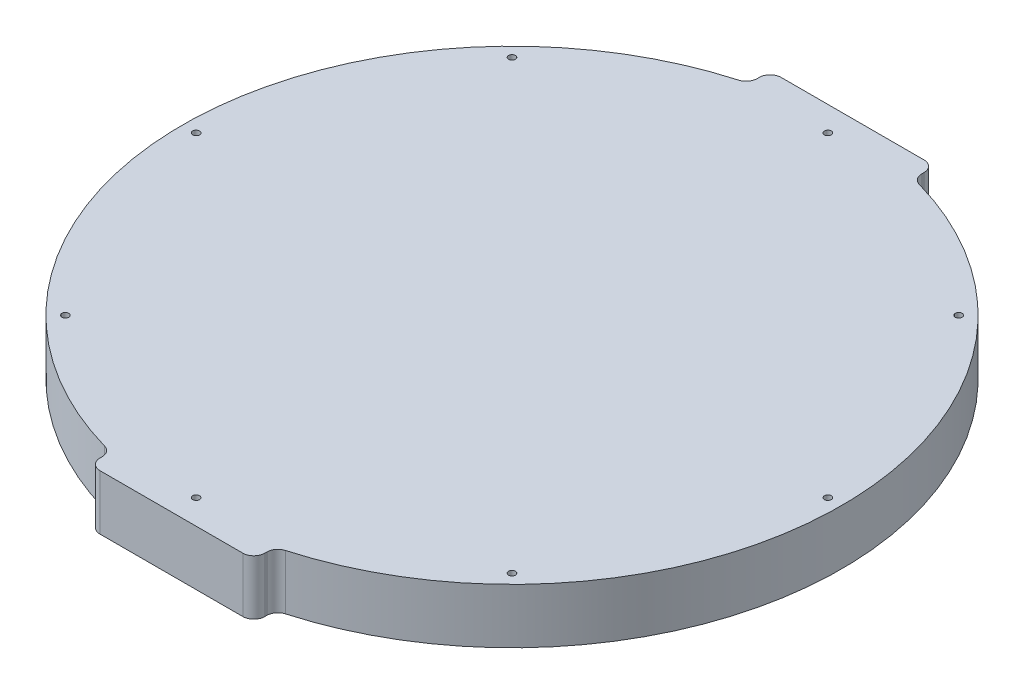
SolidWorks part; units mm, degrees
material "6061 Alloy"
ref_plane "Front Plane" through (0, 0, 0) normal (0, 0, 1) x (1, 0, 0)
ref_plane "Top Plane" through (0, 0, 0) normal (0, 1, 0) x (1, 0, 0)
ref_plane "Right Plane" through (0, 0, 0) normal (1, 0, 0) x (0, 0, -1)
sketch "Sketch2" plane through (0, 0, 0) normal (0, 1, 0) x (1, 0, 0)
  circle A0 centre (0, 0) radius 76.2
extrude "Boss-Extrude1" add sketch "Sketch2" along normal blind 12.7
sketch "Sketch3" plane through (0, 0, 0) normal (0, 0, 1) x (1, 0, 0)
  line L0 (0, 0) -> (-19.05, 0)
  line L1 (-19.05, 0) -> (-19.05, 12.7)
  line L2 (-19.05, 12.7) -> (19.05, 12.7)
  line L3 (19.05, 12.7) -> (19.05, 0)
  line L4 (0, 0) -> (19.05, 0)
extrude "Boss-Extrude2" add sketch "Sketch3" along normal blind 78.74 and the other way blind 78.74
fillet "Fillet1" radius 2.54 8 edges at (19.05, 6.35, 73.7803) (19.05, 6.35, -73.7803) (19.05, 6.35, 78.74) (-19.05, 6.35, -73.7803) (-19.05, 6.35, 73.7803) (-19.05, 6.35, 78.74) (-19.05, 6.35, -78.74) (19.05, 6.35, -78.74)
sketch "Sketch4" plane through (0, 12.7, 0) normal (0, 1, 0) x (1, 0, 0)
  circle A0 centre (73.025, 0) radius 0.7937
  circle A1 centre (51.6365, -51.6365) radius 0.7937
  circle A2 centre (0, -73.025) radius 0.7937
  circle A3 centre (-51.6365, -51.6365) radius 0.7937
  circle A4 centre (-73.025, 0) radius 0.7937
  circle A5 centre (-51.6365, 51.6365) radius 0.7937
  circle A6 centre (0, 73.025) radius 0.7937
  circle A7 centre (51.6365, 51.6365) radius 0.7937
  point P18 (0, 0)
  dimension "D1" = 8
extrude "Cut-Extrude1" cut sketch "Sketch4" against normal through all
